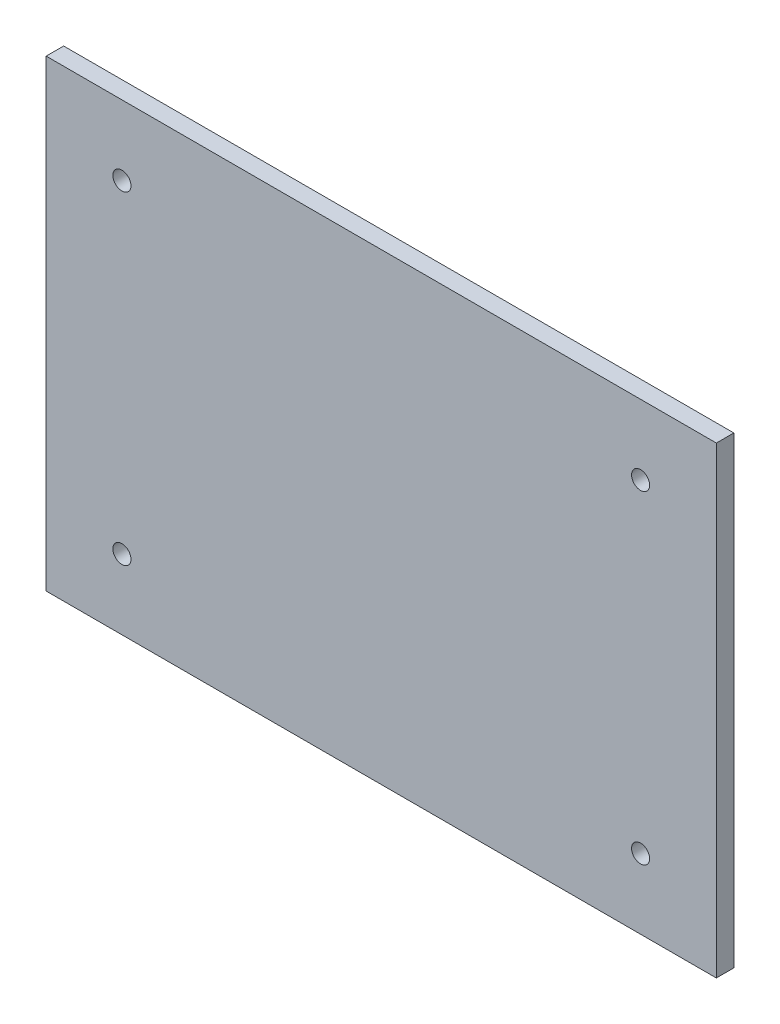
SolidWorks part; units mm, degrees
ref_plane "Alzado" through (0, 0, 0) normal (0, 0, 1) x (1, 0, 0)
ref_plane "Planta" through (0, 0, 0) normal (0, 1, 0) x (1, 0, 0)
ref_plane "Vista lateral" through (0, 0, 0) normal (1, 0, 0) x (0, 0, -1)
sketch "Croquis1" plane through (0, 0, 0) normal (0, 0, 1) x (1, 0, 0)
  line L1 (-57.5, -39.75) -> (57.5, -39.75)
  line L2 (-57.5, -39.75) -> (-57.5, 39.75)
  line L3 (-57.5, 39.75) -> (57.5, 39.75)
  line L4 (57.5, -39.75) -> (57.5, 39.75)
  line L5 (-57.5, -39.75) -> (57.5, 39.75) construction
  line L6 (-57.5, 39.75) -> (57.5, -39.75) construction
  point P0 (0, 0)
  dimension "D1" = 115
  dimension "D2" = 79.5
extrude "Saliente-Extruir1" add sketch "Croquis1" along normal blind 3
sketch "Croquis2" plane through (0, 0, 3) normal (0, 0, 1) x (1, 0, 0)
  line L0 (57.5, 39.75) -> (-57.5, 39.75) construction
  line L1 (-57.5, -39.75) -> (57.5, -39.75) construction
  line L2 (-57.5, 39.75) -> (-57.5, -39.75) construction
  line L3 (57.5, -39.75) -> (57.5, 39.75) construction
  circle A0 centre (-44.5, 27.75) radius 1.55
  circle A1 centre (44.5, 27.75) radius 1.55
  circle A2 centre (44.5, -27.75) radius 1.55
  circle A3 centre (-44.5, -27.75) radius 1.55
  dimension "D2" = 12
  dimension "D3" = 12
  dimension "D4" = 12
  dimension "D5" = 13
  dimension "D6" = 13
  dimension "D7" = 13
  dimension "D8" = 3.1
  dimension "D1" = 12
  dimension "D9" = 13
extrude "Cortar-Extruir1" cut sketch "Croquis2" against normal blind 3
